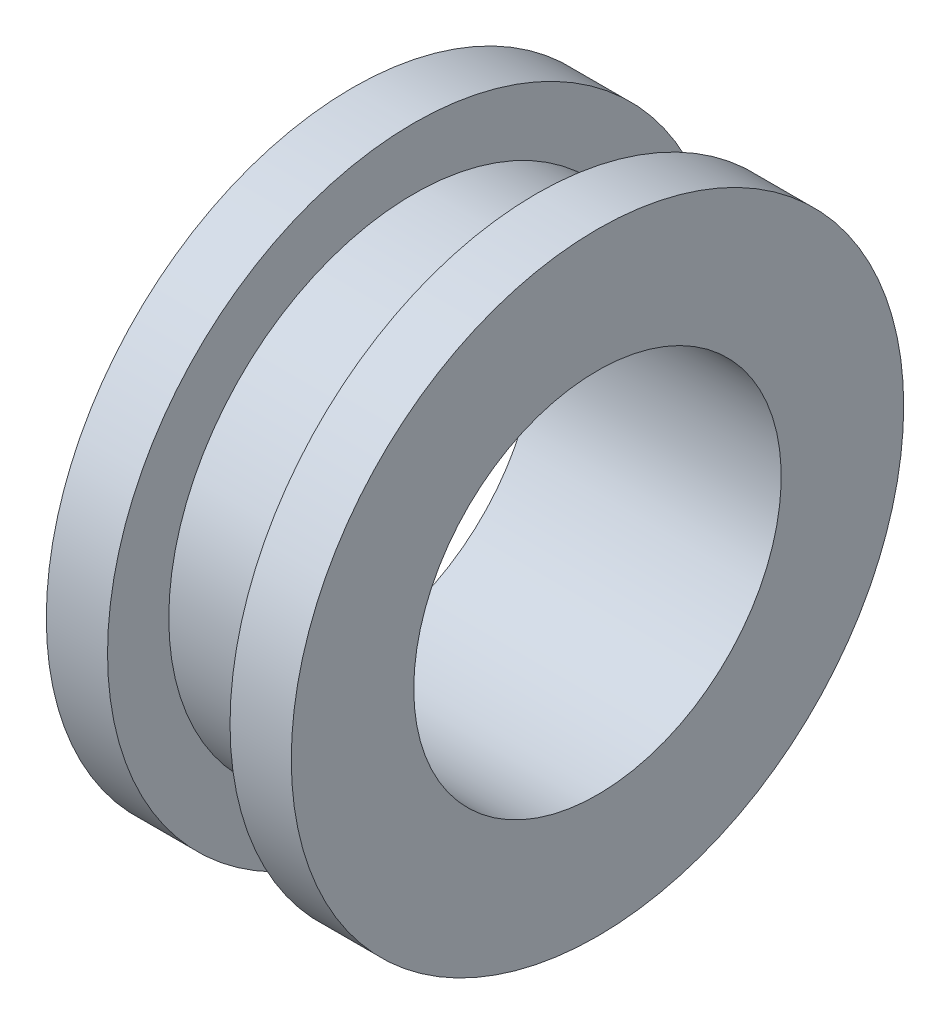
SolidWorks part; units mm, degrees
material "ｴﾁﾚﾝﾌﾟﾛﾋﾟﾚﾝｺﾞﾑ(EPDM) 60 Durometer"
ref_plane "Front Plane" through (0, 0, 0) normal (0, 0, 1) x (1, 0, 0)
ref_plane "Top Plane" through (0, 0, 0) normal (0, 1, 0) x (1, 0, 0)
ref_plane "Right Plane" through (0, 0, 0) normal (1, 0, 0) x (0, 0, -1)
sketch "ｽｹｯﾁ1" plane through (0, 0, 0) normal (0, 0, 1) x (1, 0, 0)
  line L0 (0, 0) -> (4.9012, 0) construction
  line L1 (4.5, 7.5) -> (6, 7.5)
  line L2 (0, 4.5) -> (6, 4.5)
  line L3 (0, 4.5) -> (0, 7.5)
  line L4 (0, 7.5) -> (1.5, 7.5)
  line L5 (6, 4.5) -> (6, 7.5)
  line L6 (0, 0) -> (0, 2.9944) construction
  line L7 (3, 4.5) -> (3, 9.9115) construction
  line L9 (1.5, 7.5) -> (1.5, 6)
  line L10 (1.5, 6) -> (4.5, 6)
  line L11 (4.5, 7.5) -> (4.5, 6)
  point P13 (5.0122, 6)
  dimension "D1" = 9
  dimension "D2" = 12
  dimension "D3" = 6
  dimension "D4" = 3
  dimension "D5" = 15
revolve "回転1" add sketch "ｽｹｯﾁ1" angle 360 about L0
